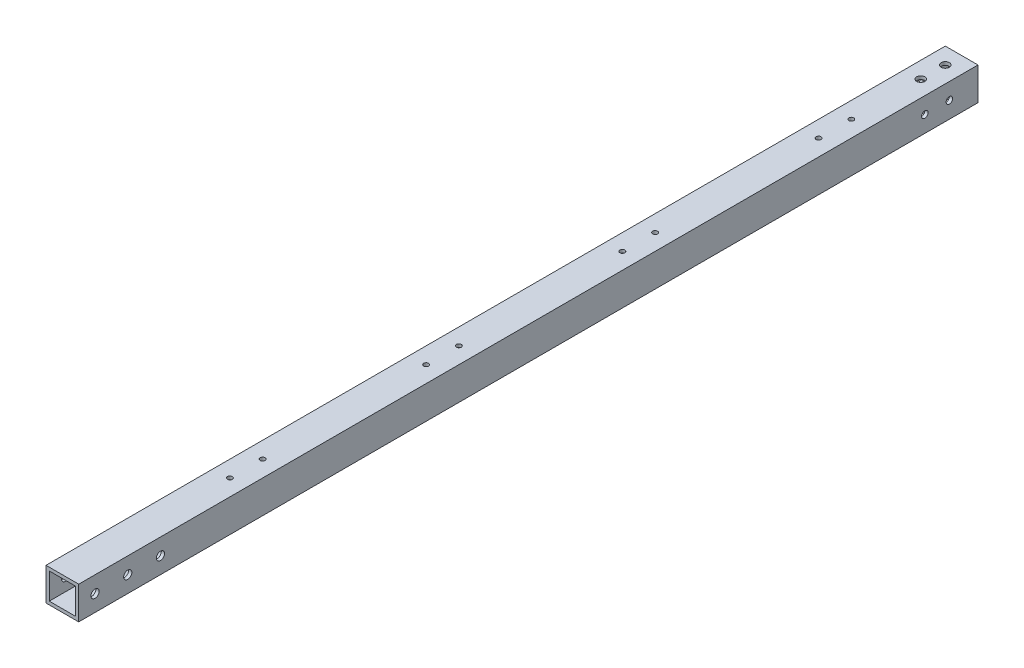
SolidWorks part; units mm, degrees
material "3.0205 (EN-AW 1200)"
ref_plane "前视基准面" through (0, 0, 0) normal (0, 0, 1) x (1, 0, 0)
ref_plane "上视基准面" through (0, 0, 0) normal (0, 1, 0) x (1, 0, 0)
ref_plane "右视基准面" through (0, 0, 0) normal (1, 0, 0) x (0, 0, -1)
sketch "草图1" plane through (0, 0, 0) normal (0, 0, 1) x (1, 0, 0)
  line L1 (-10, -10) -> (10, -10)
  line L2 (-10, -10) -> (-10, 10)
  line L3 (-10, 10) -> (10, 10)
  line L4 (10, -10) -> (10, 10)
  line L5 (-10, -10) -> (10, 10) construction
  line L6 (-10, 10) -> (10, -10) construction
  line L7 (-8, -8) -> (8, -8)
  line L8 (-8, -8) -> (-8, 8)
  line L9 (-8, 8) -> (8, 8)
  line L10 (8, -8) -> (8, 8)
  line L11 (-8, -8) -> (8, 8) construction
  line L12 (-8, 8) -> (8, -8) construction
  point P0 (0, 0)
  point P6 (0, 0)
  dimension "D1" = 16
  dimension "D2" = 20
  dimension "D3" = 20
extrude "凸台-拉伸1" add sketch "草图1" along normal blind 550
sketch "Sketch2" plane through (0, -10, 0) normal (0, -1, 0) x (1, 0, 0)
  line L0 (0, 0) -> (0, 33.3256) construction
  line L1 (-10, 0) -> (10, 0) construction
  circle A0 centre (0, 10) radius 2.5
  circle A1 centre (0, 25) radius 2.5
  dimension "D1" = 5
  dimension "D2" = 5
  dimension "D4" = 15
  dimension "D3" = 10
extrude "Cut-Extrude2" cut sketch "Sketch2" against normal blind 20
sketch "Sketch3" plane through (-10, 0, 0) normal (-1, 0, 0) x (0, 0, 1)
  line L0 (0, 0) -> (112.8988, 0) construction
  circle A0 centre (17.5, 0) radius 2
  circle A1 centre (32.5, 0) radius 2
  dimension "D1" = 4
  dimension "D2" = 4
  dimension "D4" = 17.5
  dimension "D3" = 15
extrude "Cut-Extrude3" cut sketch "Sketch3" against normal blind 20
sketch "Sketch4" plane through (10, 0, 0) normal (1, 0, 0) x (0, 0, -1)
  line L0 (-550, 0) -> (-458.2264, 0) construction
  line L1 (-550, -10) -> (-550, 10) construction
  circle A0 centre (-540, 0) radius 2.5
  circle A1 centre (-520, 0) radius 2.5
  circle A2 centre (-500, 0) radius 2.5
  dimension "D4" = 5
  dimension "D5" = 5
  dimension "D6" = 5
  dimension "D1" = 10
  dimension "D2" = 20
  dimension "D3" = 20
extrude "Cut-Extrude4" cut sketch "Sketch4" against normal blind 20
sketch "Sketch6" plane through (0, -10, 0) normal (0, -1, 0) x (1, 0, 0)
  line L0 (0, 0) -> (0, 550) construction
  line L1 (-10, 550) -> (10, 550) construction
  circle A0 centre (0, 67.5) radius 1.5
  circle A1 centre (0, 87.5) radius 1.5
  dimension "D2" = 20
  dimension "D3" = 3
  dimension "D4" = 3
  dimension "D1" = 67.5
extrude "Cut-Extrude6" cut sketch "Sketch6" against normal blind 20
pattern_linear "LPattern1" count 4 spacing 120 along (0, 0, 1) of "Cut-Extrude6"
